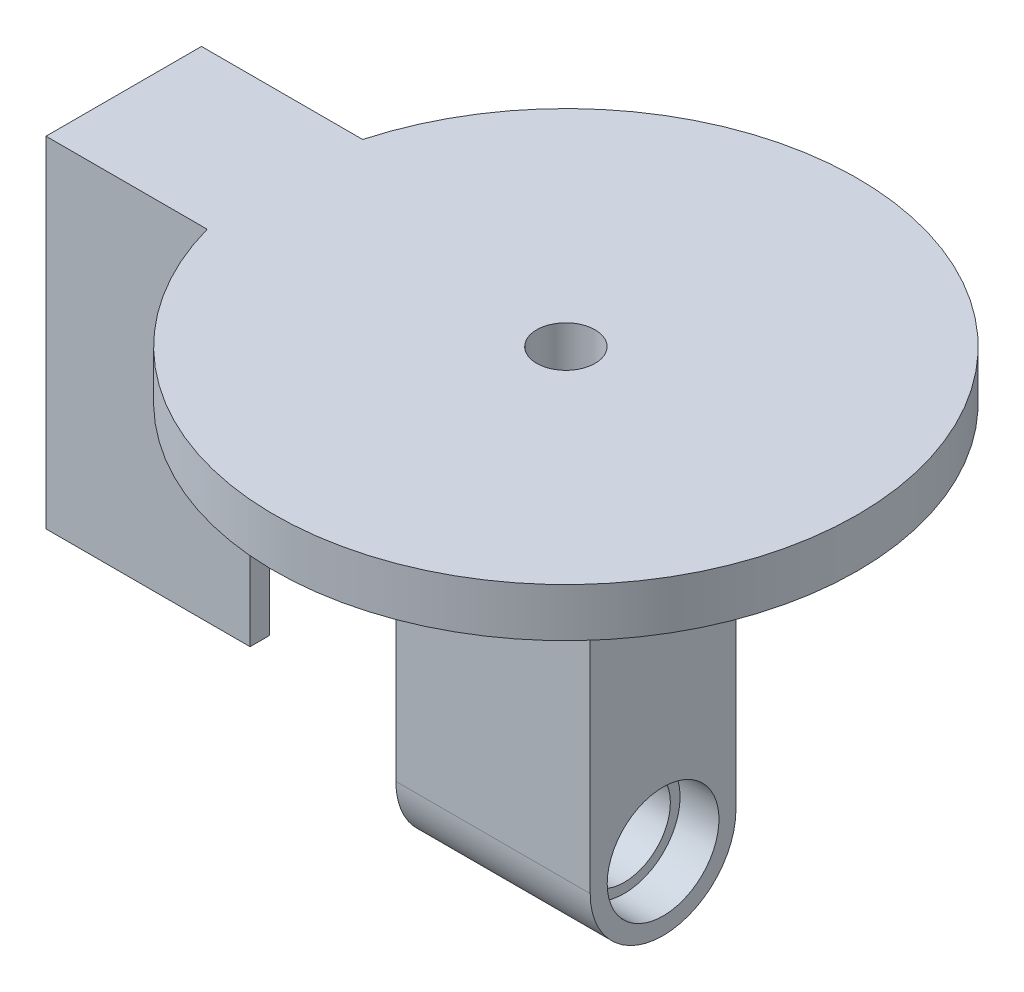
SolidWorks part; units mm, degrees
ref_plane "Front Plane" through (0, 0, 0) normal (0, 0, 1) x (1, 0, 0)
ref_plane "Top Plane" through (0, 0, 0) normal (0, 1, 0) x (1, 0, 0)
ref_plane "Right Plane" through (0, 0, 0) normal (1, 0, 0) x (0, 0, -1)
sketch "Sketch1" plane through (0, 0, 0) normal (0, 1, 0) x (1, 0, 0)
  line L5 (0, 30) -> (0, -30) construction
  line L6 (-30, 0) -> (30, 0) construction
  circle A2 centre (0, 0) radius 30
  dimension "D1" = 60
extrude "Boss-Extrude1" add sketch "Sketch1" along normal blind 5
ref_plane "Plane3" through (10, 0, 0) normal (1, 0, 0) x (0, 0, -1)
sketch "Sketch8" plane through (10, 0, 0) normal (1, 0, 0) x (0, 0, -1)
  line L0 (0, 0) -> (0, -35) construction
  line L3 (-7.5, 0) -> (-7.5, -35)
  line L4 (-7.5, 0) -> (7.5, 0)
  line L6 (7.5, 0) -> (7.5, -35)
  line L7 (-7.5, 0) -> (7.5, -35) construction
  line L8 (-7.5, -35) -> (7.5, 0) construction
  circle A5 centre (0, -35) radius 4.75
  arc A11 (-7.5, -35) -> (7.5, -35) centre (0, -35) ccw
  point P5 (0, -17.5)
  dimension "D2" = 15
  dimension "D4" = 9.5
  dimension "D1" = 35
extrude "Boss-Extrude3" add sketch "Sketch8" against normal blind 10
sketch "Sketch9" plane through (10, 0, 0) normal (-1, 0, 0) x (0, 0, 1)
  circle A0 centre (0, -35) radius 5.75
  dimension "D1" = 11.5
extrude "Cut-Extrude3" cut sketch "Sketch9" along normal blind 4
mirror "Mirror1" about plane through (0, 0, 0) normal (1, 0, 0) of "Boss-Extrude3", "Cut-Extrude3"
sketch "Sketch16" plane through (0, 0, 0) normal (0, -1, 0) x (-1, 0, 0)
  line L1 (24.5, 8) -> (45.5, 8)
  line L2 (24.5, 8) -> (24.5, -8)
  line L3 (24.5, -8) -> (45.5, -8)
  line L5 (10, 7.5) -> (10, -7.5) construction
  line L6 (24.5, 0) -> (30, 0) construction
  line L7 (45.5, 8) -> (45.5, -8)
  dimension "D3" = 21
  dimension "D1" = 16
  dimension "D2" = 14.5
extrude "Boss-Extrude7" add sketch "Sketch16" along normal blind 10 and the other way up to surface other way up to face at (0, 5, 30)
sketch "Sketch17" plane through (0, -10, 0) normal (0, -1, 0) x (1, 0, 0)
  line L0 (-24.5, 8) -> (-24.5, 6)
  line L1 (-24.5, -8) -> (-24.5, 8) construction
  line L2 (-24.5, 6) -> (-45.5, 6)
  line L3 (-45.5, 8) -> (-45.5, -8) construction
  line L4 (-45.5, 6) -> (-45.5, 8)
  line L5 (-45.5, 8) -> (-24.5, 8)
  line L6 (-24.5, -8) -> (-24.5, -6)
  line L7 (-24.5, -6) -> (-45.5, -6)
  line L8 (-45.5, -6) -> (-45.5, -8)
  line L9 (-45.5, -8) -> (-24.5, -8)
  dimension "D1" = 2
extrude "Boss-Extrude8" add sketch "Sketch17" along normal blind 20
sketch "Sketch18" plane through (0, 5, 0) normal (0, 1, 0) x (1, 0, 0)
  circle A0 centre (0, 0) radius 3
  dimension "D1" = 6
extrude "Cut-Extrude4" cut sketch "Sketch18" against normal blind 8
